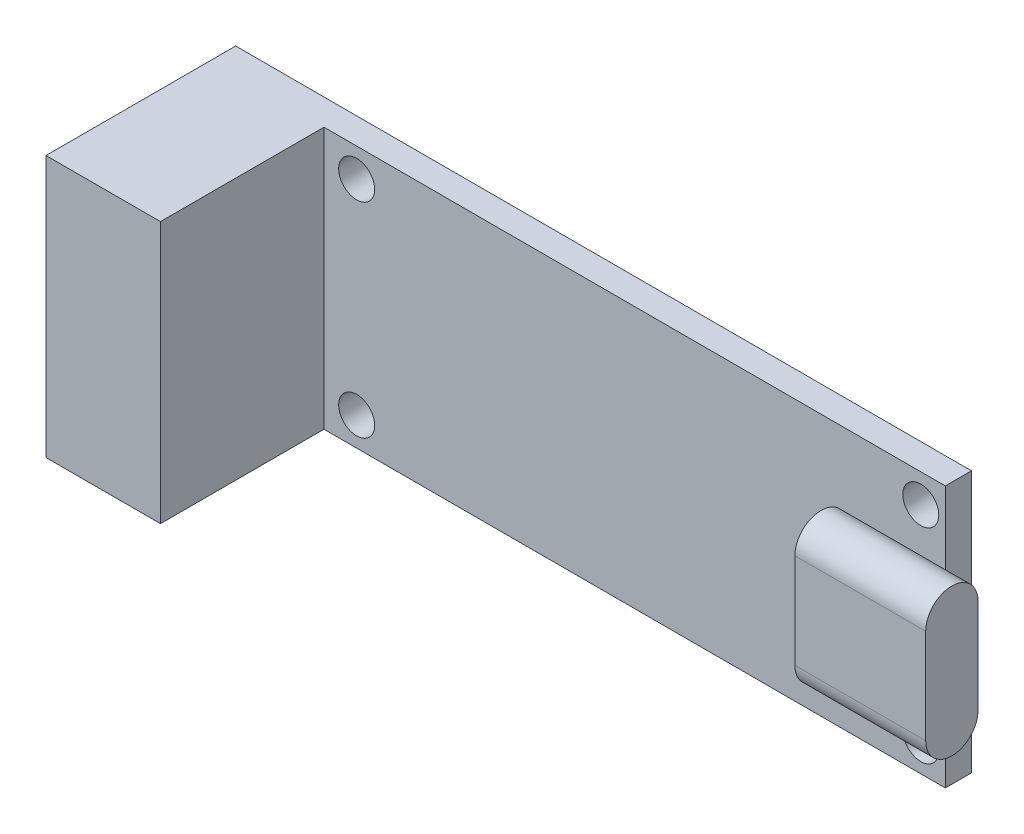
SolidWorks part; units mm, degrees
ref_plane "Płaszczyzna przednia" through (0, 0, 0) normal (0, 0, 1) x (1, 0, 0)
ref_plane "Płaszczyzna górna" through (0, 0, 0) normal (0, 1, 0) x (1, 0, 0)
ref_plane "Płaszczyzna prawa" through (0, 0, 0) normal (1, 0, 0) x (0, 0, -1)
sketch "Sketch1" plane through (0, 0, 0) normal (0, 0, 1) x (1, 0, 0)
  line L0 (9, 14.25) -> (9, 1.75) construction
  line L1 (0, 0) -> (45, 0)
  line L2 (0, 0) -> (0, 16)
  line L3 (0, 16) -> (45, 16)
  line L4 (45, 0) -> (45, 16)
  line L5 (9, 1.75) -> (43.5, 1.75) construction
  line L6 (43.5, 1.75) -> (43.5, 14.25) construction
  line L7 (43.5, 14.25) -> (9, 14.25) construction
  line L8 (9, 16) -> (9, 14.25) construction
  line L9 (9, 0) -> (9, 1.75) construction
  circle A0 centre (9, 14.25) radius 1.1
  circle A1 centre (9, 1.75) radius 1.1
  circle A2 centre (43.5, 14.25) radius 1.1
  circle A3 centre (43.5, 1.75) radius 1.1
  dimension "D3" = 2.2
  dimension "D4" = 9
  dimension "D1" = 16
  dimension "D2" = 45
  dimension "D5" = 43.5
  dimension "D6" = 12.5
extrude "Boss-Extrude1" add sketch "Sketch1" along normal blind 1.6
sketch "Sketch2" plane through (45, 0, 0) normal (1, 0, 0) x (0, 0, -1)
  line L0 (-3.2, 10.9) -> (-3.2, 5.1) construction
  line L1 (-1.6, 10.9) -> (-1.6, 5.1)
  line L2 (-4.8, 10.9) -> (-4.8, 5.1)
  line L3 (-1.6, 0) -> (-1.6, 16) construction
  line L4 (0, 8) -> (-3.2, 8) construction
  line L5 (0, 0) -> (0, 16) construction
  arc A0 (-1.6, 10.9) -> (-4.8, 10.9) centre (-3.2, 10.9) ccw
  arc A1 (-4.8, 5.1) -> (-1.6, 5.1) centre (-3.2, 5.1) ccw
  point P2 (-3.2, 8)
  point P9 (-3.2, 12.5)
  point P10 (-3.2, 3.5)
  dimension "D1" = 3.2
  dimension "D2" = 9
extrude "Boss-Extrude2" add sketch "Sketch2" along normal blind 2 and the other way blind 6
sketch "Sketch3" plane through (0, 0, 1.6) normal (0, 0, 1) x (1, 0, 0)
  line L0 (0, 0) -> (45, 0) construction
  line L1 (0, 16) -> (7, 16)
  line L2 (0, 16) -> (0, 0)
  line L3 (0, 0) -> (7, 0)
  line L4 (7, 16) -> (7, 0)
  dimension "D1" = 7
extrude "Boss-Extrude3" add sketch "Sketch3" along normal blind 10
